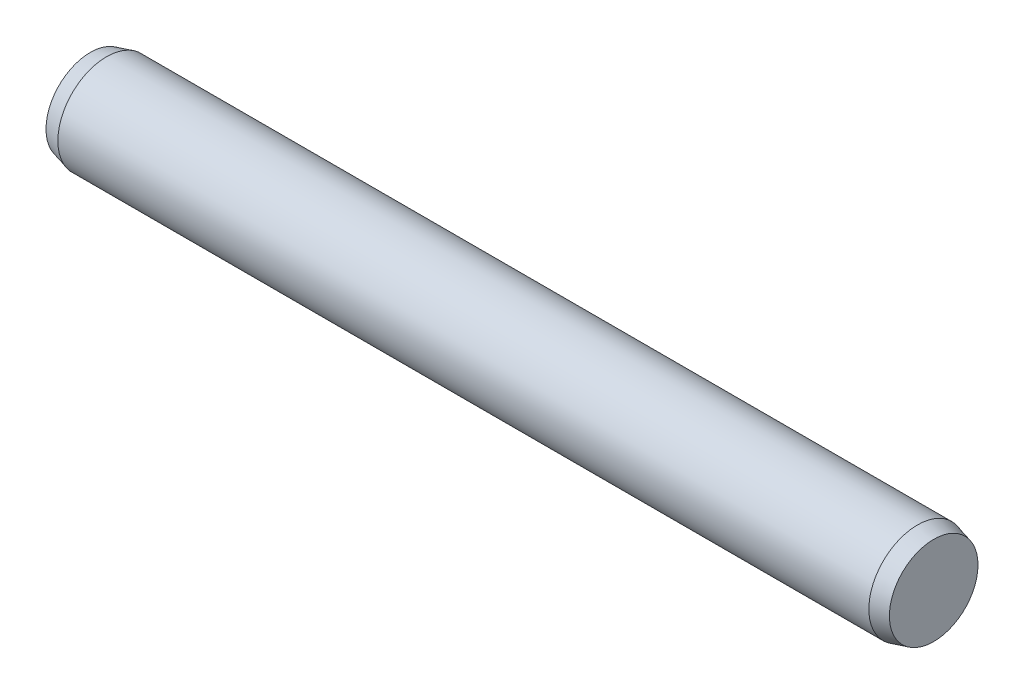
SolidWorks part; units mm, degrees
ref_plane "Front Plane" through (0, 0, 0) normal (0, 0, 1) x (1, 0, 0)
ref_plane "Top Plane" through (0, 0, 0) normal (0, 1, 0) x (1, 0, 0)
ref_plane "Right Plane" through (0, 0, 0) normal (1, 0, 0) x (0, 0, -1)
sketch "Sketch1" plane through (0, 0, 0) normal (0, 0, 1) x (1, 0, 0)
  line L0 (-12.5, 0) -> (12.5, 0) construction
  line L1 (12.5, 1.5) -> (12.5, -1.5) construction
  line L2 (-12.5, 1.5) -> (-12.5, -1.5) construction
  line L3 (13, 1.5) -> (13, -1.5) construction
  line L4 (-13, 1.5) -> (-13, -1.5) construction
  line L5 (-12.5, 0) -> (-13, 0) construction
  line L6 (12.5, 0) -> (13, 0) construction
  dimension "Dia" = 3
  dimension "C" = 0.5
  dimension "D1" = 0.5
  dimension "Length" = 26
sketch "Sketch2" plane through (0, 0, 0) normal (1, 0, 0) x (0, 0, -1)
  circle A0 centre (0, 0) radius 1.5
extrude "Extrude1" add sketch "Sketch2" against normal up to vertex (12.5 mm away) and the other way up to vertex (12.5 mm away) up to point (-12.5, 1.5, 0) other way up to point (12.5, 1.5, 0)
sketch "Sketch3" plane through (12.5, 0, 0) normal (1, 0, 0) x (0, 0, -1)
  circle A1 centre (0, 0) radius 1.5
  circle A2 centre (0, 0) radius 1.5
  dimension "D1" = 0
extrude "Extrude2" add sketch "Sketch3" along normal up to vertex (0.5 mm away) draft 15 up to point (13, 0, 0)
sketch "Sketch4" plane through (-12.5, 0, 0) normal (-1, 0, 0) x (0, 0, 1)
  circle A1 centre (0, 0) radius 1.5
  circle A2 centre (0, 0) radius 1.5
  dimension "D1" = 0
extrude "Extrude3" add sketch "Sketch4" along normal up to vertex (0.5 mm away) draft 15 up to point (-13, 0, 0)
equation "\"D1@Sketch1\" = \"C@Sketch1\""
